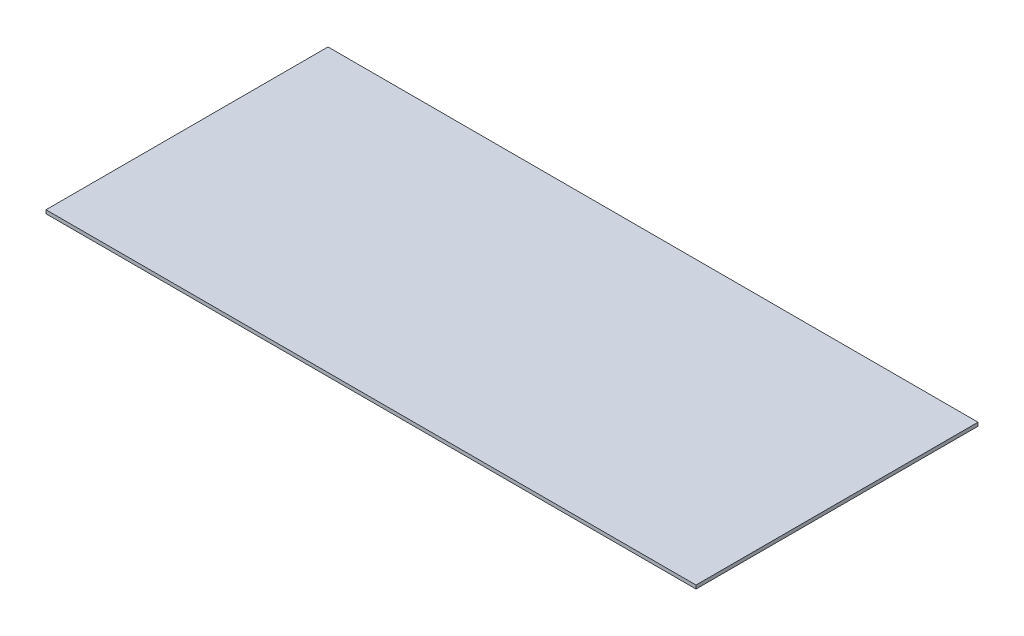
SolidWorks part; units mm, degrees
ref_plane "Alzado" through (0, 0, 0) normal (0, 0, 1) x (1, 0, 0)
ref_plane "Planta" through (0, 0, 0) normal (0, 1, 0) x (1, 0, 0)
ref_plane "Vista lateral" through (0, 0, 0) normal (1, 0, 0) x (0, 0, -1)
sketch "Croquis1" plane through (0, 0, 0) normal (0, 1, 0) x (1, 0, 0)
  line L1 (461, -200) -> (-461, -200)
  line L2 (461, -200) -> (461, 200)
  line L3 (461, 200) -> (-461, 200)
  line L4 (-461, -200) -> (-461, 200)
  line L5 (461, -200) -> (-461, 200) construction
  line L6 (461, 200) -> (-461, -200) construction
  point P0 (0, 0)
  dimension "D1" = 922
  dimension "D2" = 400
extrude "Extruir1" add sketch "Croquis1" along normal blind 5
